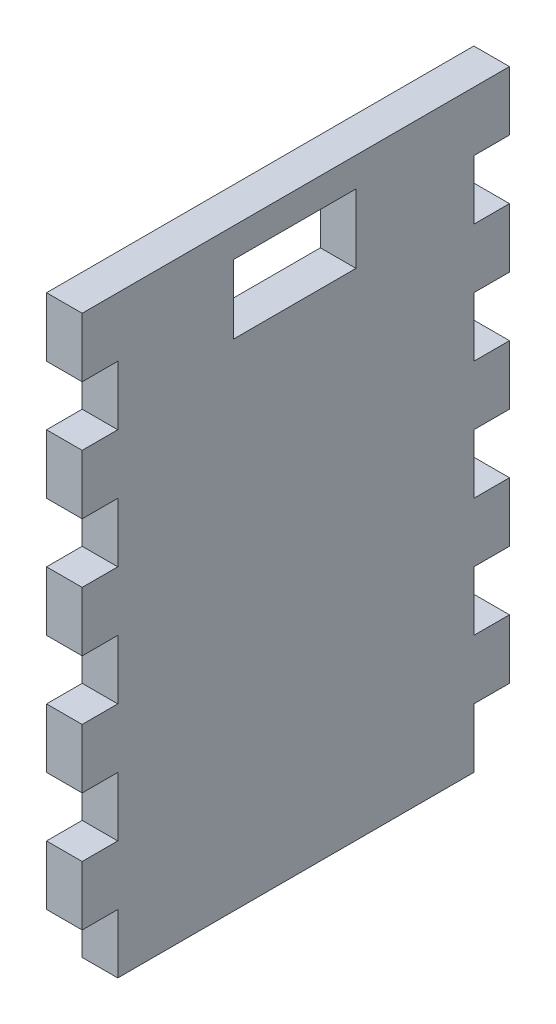
SolidWorks part; units mm, degrees
ref_plane "Plano frontal" through (0, 0, 0) normal (0, 0, 1) x (1, 0, 0)
ref_plane "Plano superior" through (0, 0, 0) normal (0, 1, 0) x (1, 0, 0)
ref_plane "Plano direito" through (0, 0, 0) normal (1, 0, 0) x (0, 0, -1)
sketch "Esboço1" plane through (0, 0, 0) normal (1, 0, 0) x (0, 0, -1)
  line L0 (15.9843, 25.1066) -> (15.9843, 20.1066)
  line L1 (-20.0157, 25.1066) -> (15.9843, 25.1066)
  line L5 (3.0535, 22.6466) -> (-7.2465, 22.6466)
  line L6 (3.0535, 22.6466) -> (3.0535, 16.8466)
  line L7 (3.0535, 16.8466) -> (-7.2465, 16.8466)
  line L8 (-7.2465, 22.6466) -> (-7.2465, 16.8466)
  line L9 (15.9843, 20.1066) -> (12.9843, 20.1066)
  line L10 (12.9843, 20.1066) -> (12.9843, 15.1066)
  line L11 (12.9843, 15.1066) -> (15.9843, 15.1066)
  line L12 (15.9843, 15.1066) -> (15.9843, 10.1066)
  line L13 (15.9843, 10.1066) -> (12.9843, 10.1066)
  line L14 (12.9843, 10.1066) -> (12.9843, 5.1066)
  line L15 (12.9843, 5.1066) -> (15.9843, 5.1066)
  line L16 (15.9843, 5.1066) -> (15.9843, 0.1066)
  line L17 (15.9843, 0.1066) -> (12.9843, 0.1066)
  line L18 (12.9843, 0.1066) -> (12.9843, -4.8934)
  line L19 (12.9843, -4.8934) -> (15.9843, -4.8934)
  line L20 (15.9843, -4.8934) -> (15.9843, -9.8934)
  line L21 (15.9843, -9.8934) -> (12.9843, -9.8934)
  line L22 (12.9843, -9.8934) -> (12.9843, -14.8934)
  line L23 (12.9843, -14.8934) -> (15.9843, -14.8934)
  line L24 (15.9843, -14.8934) -> (15.9843, -19.8934)
  line L25 (15.9843, -19.8934) -> (12.9843, -19.8934)
  line L26 (12.9843, -19.8934) -> (12.9843, -24.8934)
  line L28 (12.9843, -24.8934) -> (15.9843, -24.8934) [skipped]
  line L29 (-17.0157, -24.8934) -> (12.9843, -24.8934)
  line L30 (-20.0157, 25.1066) -> (-20.0157, 20.1066)
  line L34 (-20.0157, 15.1066) -> (-20.0157, 10.1066)
  line L38 (-20.0157, 5.1066) -> (-20.0157, 0.1066)
  line L42 (-20.0157, -4.8934) -> (-20.0157, -9.8934)
  line L46 (-20.0157, -14.8934) -> (-20.0157, -19.8934)
  line L47 (-20.0157, 20.1066) -> (-17.0157, 20.1066)
  line L48 (-20.0157, 15.1066) -> (-17.0157, 15.1066)
  line L49 (-17.0157, -19.8934) -> (-17.0157, -24.8934)
  line L50 (-17.0157, -9.8934) -> (-17.0157, -14.8934)
  line L51 (-17.0157, 0.1066) -> (-17.0157, -4.8934)
  line L52 (-17.0157, 10.1066) -> (-17.0157, 5.1066)
  line L53 (-17.0157, 20.1066) -> (-17.0157, 15.1066)
  line L54 (-20.0157, 10.1066) -> (-17.0157, 10.1066)
  line L55 (-23.0157, 20.1066) -> (-23.0157, 15.1066) [skipped]
  line L56 (-23.0157, 10.1066) -> (-23.0157, 5.1066) [skipped]
  line L57 (-23.0157, 0.1066) -> (-23.0157, -4.8934) [skipped]
  line L58 (-23.0157, -9.8934) -> (-23.0157, -14.8934) [skipped]
  line L59 (-23.0157, -19.8934) -> (-23.0157, -24.8934) [skipped]
  line L60 (-20.0157, 20.1066) -> (-23.0157, 20.1066) [skipped]
  line L61 (-23.0157, 15.1066) -> (-20.0157, 15.1066) [skipped]
  line L62 (-20.0157, 10.1066) -> (-23.0157, 10.1066) [skipped]
  line L63 (-23.0157, 5.1066) -> (-20.0157, 5.1066) [skipped]
  line L64 (-20.0157, 0.1066) -> (-23.0157, 0.1066) [skipped]
  line L65 (-23.0157, -4.8934) -> (-20.0157, -4.8934) [skipped]
  line L66 (-20.0157, -9.8934) -> (-23.0157, -9.8934) [skipped]
  line L67 (-23.0157, -14.8934) -> (-20.0157, -14.8934) [skipped]
  line L68 (-20.0157, -19.8934) -> (-23.0157, -19.8934) [skipped]
  line L69 (-20.0157, 5.1066) -> (-17.0157, 5.1066)
  line L70 (-20.0157, 0.1066) -> (-17.0157, 0.1066)
  line L71 (-20.0157, -4.8934) -> (-17.0157, -4.8934)
  line L72 (-20.0157, -9.8934) -> (-17.0157, -9.8934)
  line L73 (-20.0157, -14.8934) -> (-17.0157, -14.8934)
  line L74 (-20.0157, -19.8934) -> (-17.0157, -19.8934)
  point P13 (0, 0)
  point P19 (0, 0)
  dimension "D1" = 5
  dimension "D2" = 36
  dimension "D3" = 10.3
  dimension "D4" = 5.8
  dimension "D5" = 5
  dimension "D6" = 2.46
  dimension "D7" = 3
  dimension "D9" = 30
  dimension "D10" = 3
  dimension "D11" = 5
  dimension "D12" = 3
  dimension "D13" = 3
  dimension "D8" = 2
extrude "Ressalto-extrusão1" add sketch "Esboço1" along normal blind 3
sketch "Esboço2" plane through (3, 0, 0) normal (1, 0, 0) x (0, 0, -1)
